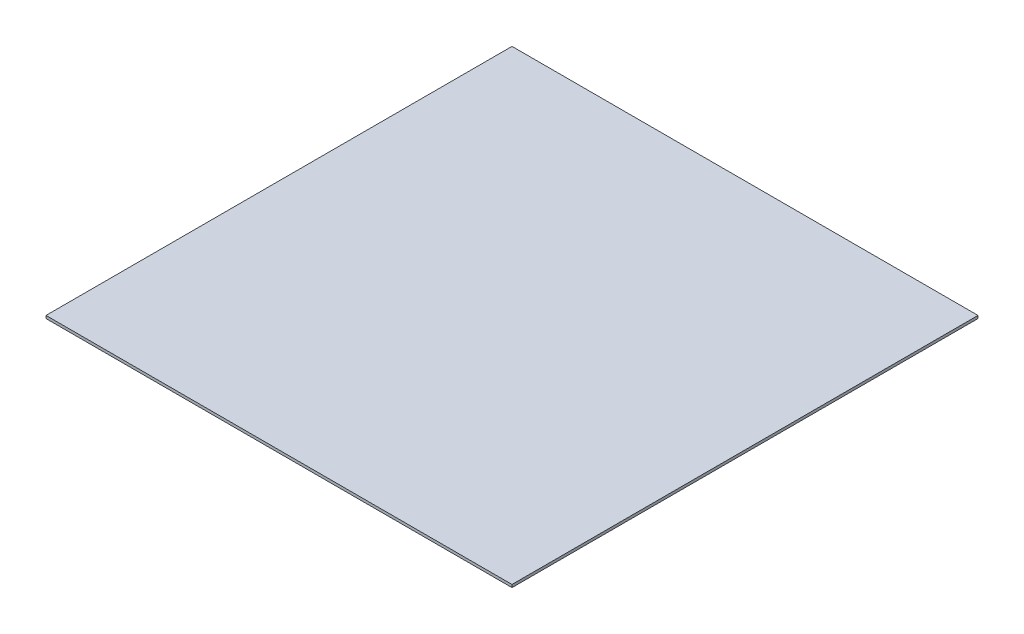
SolidWorks part; units mm, degrees
ref_plane "Front Plane" through (0, 0, 0) normal (0, 0, 1) x (1, 0, 0)
ref_plane "Top Plane" through (0, 0, 0) normal (0, 1, 0) x (1, 0, 0)
ref_plane "Right Plane" through (0, 0, 0) normal (1, 0, 0) x (0, 0, -1)
sketch "Sketch1" plane through (0, 0, 0) normal (0, 1, 0) x (1, 0, 0)
  line L1 (0, 0) -> (254, 0)
  line L2 (0, 0) -> (0, 254)
  line L3 (0, 254) -> (254, 254)
  line L4 (254, 0) -> (254, 254)
  dimension "D1" = 254
  dimension "D2" = 254
extrude "Boss-Extrude1" add sketch "Sketch1" along normal blind 1.5
